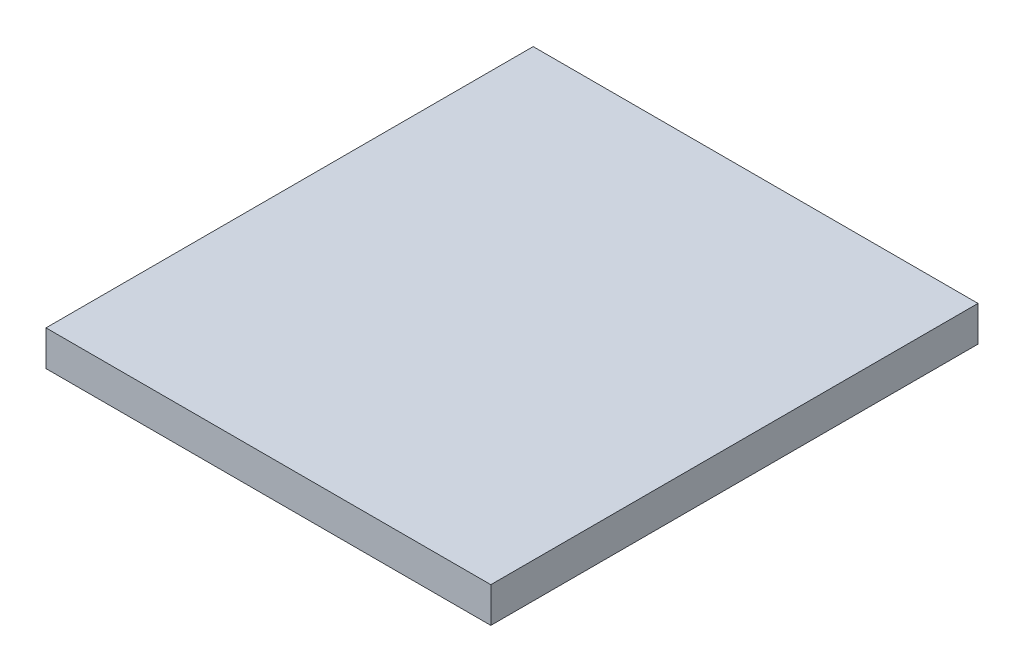
SolidWorks part; units mm, degrees
ref_plane "Front Plane" through (0, 0, 0) normal (0, 0, 1) x (1, 0, 0)
ref_plane "Top Plane" through (0, 0, 0) normal (0, 1, 0) x (1, 0, 0)
ref_plane "Right Plane" through (0, 0, 0) normal (1, 0, 0) x (0, 0, -1)
sketch "Sketch1" plane through (0, 0, 0) normal (0, 1, 0) x (1, 0, 0)
  line L1 (-31.5, 34.5) -> (31.5, 34.5)
  line L2 (-31.5, 34.5) -> (-31.5, -34.5)
  line L3 (-31.5, -34.5) -> (31.5, -34.5)
  line L4 (31.5, 34.5) -> (31.5, -34.5)
  line L5 (-31.5, 34.5) -> (31.5, -34.5) construction
  line L6 (-31.5, -34.5) -> (31.5, 34.5) construction
  point P0 (0, 0)
  dimension "D1" = 63
  dimension "D2" = 69
extrude "Boss-Extrude1" add sketch "Sketch1" along normal blind 5
